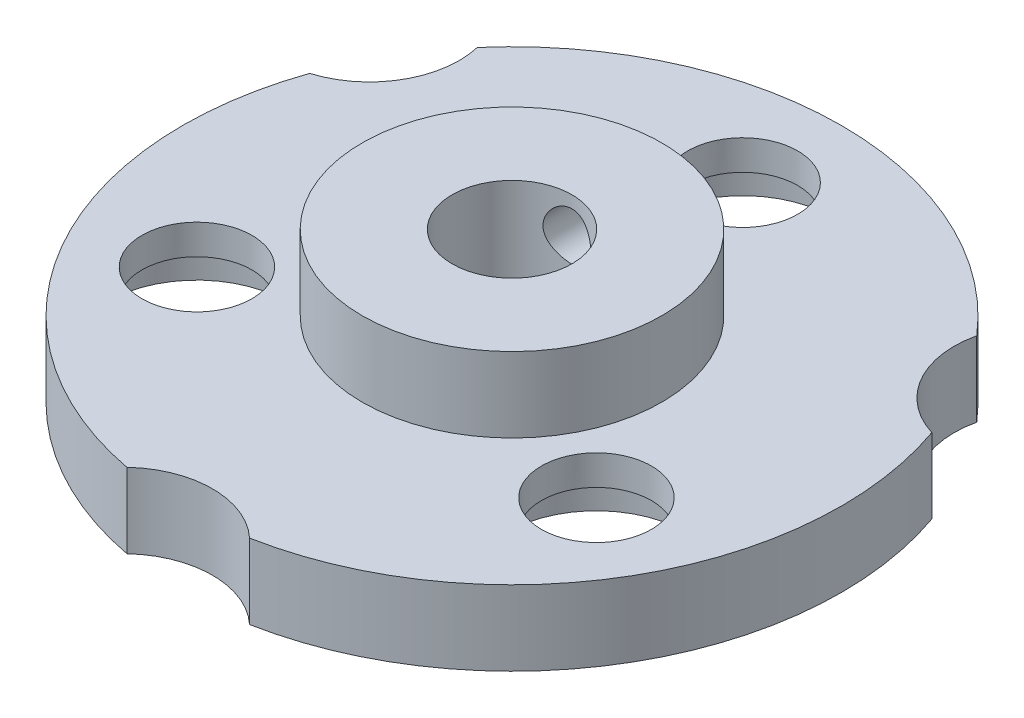
SolidWorks part; units mm, degrees
ref_plane "Plano frontal" through (0, 0, 0) normal (0, 0, 1) x (1, 0, 0)
ref_plane "Plano superior" through (0, 0, 0) normal (0, 1, 0) x (1, 0, 0)
ref_plane "Plano direito" through (0, 0, 0) normal (1, 0, 0) x (0, 0, -1)
sketch "Esboço1" plane through (0, 0, 0) normal (0, 1, 0) x (1, 0, 0)
  circle A0 centre (0, 0) radius 11
  dimension "D1" = 22
extrude "Ressalto-extrusão1" add sketch "Esboço1" along normal blind 2.5
sketch "Esboço3" plane through (0, 2.5, 0) normal (0, 1, 0) x (1, 0, 0)
  circle A1 centre (0, 7.7) radius 1.8355
  circle A2 centre (6.6684, -3.85) radius 1.8355
  circle A3 centre (-6.6684, -3.85) radius 1.8355
  dimension "D1" = 7.7
  dimension "D2" = 7.7
extrude "Corte-extrusão1" cut sketch "Esboço3" against normal blind 2.5
sketch "Esboço18" plane through (0, 2.5, 0) normal (0, 1, 0) x (1, 0, 0)
  circle A0 centre (0, 0) radius 5
  dimension "D1" = 10
extrude "Ressalto-extrusão5" add sketch "Esboço18" along normal blind 2.5
sketch "Esboço20" plane through (0, 5, 0) normal (0, 1, 0) x (1, 0, 0)
  circle A0 centre (0, 0) radius 2
  dimension "D1" = 4
extrude "Corte-extrusão5" cut sketch "Esboço20" against normal blind 5.5
hole_wizard "Broca de rosquear para tarraxa de M2x0.41" positions "3DSketch3" profile "Esboço21" hole size "M2x0.4" standard "Ansi Metric"
sketch3d "3DSketch3"
  point P0 (0.0026, 3.793, -5)
sketch "Esboço21" plane through (0.0026, 3.793, -5) normal (0, 1, 0) x (-1, 0, -0.0005)
  line L0 (0, 0) -> (0, 3)
  line L1 (0, 3) -> (0.8, 3)
  line L2 (0.8, 3) -> (0.8, 0)
  line L5 (0.8, 0) -> (0, 0)
  line L11 (0, -6.35) -> (0, 107.95) construction
  dimension "Thru Hole Dia." = 1.6
  dimension "Thru Hole Depth" = 3
sketch "Esboço22" plane through (0, 2.5, 0) normal (0, 1, 0) x (1, 0, 0)
  circle A1 centre (-11.2583, 6.5) radius 3
  circle A2 centre (0, -13) radius 3
  circle A3 centre (11.2583, 6.5) radius 3
  dimension "D1" = 6
extrude "Corte-extrusão6" cut sketch "Esboço22" against normal blind 5.5
sketch "Esboço23" plane through (0, 0, 0) normal (0, -1, 0) x (-1, 0, 0)
  circle A0 centre (-6.6684, -3.85) radius 3
  circle A1 centre (6.6684, -3.85) radius 3
  circle A2 centre (0, 7.7) radius 3
  dimension "D1" = 6
extrude "Corte-extrusão7" cut sketch "Esboço23" against normal blind 1.5
